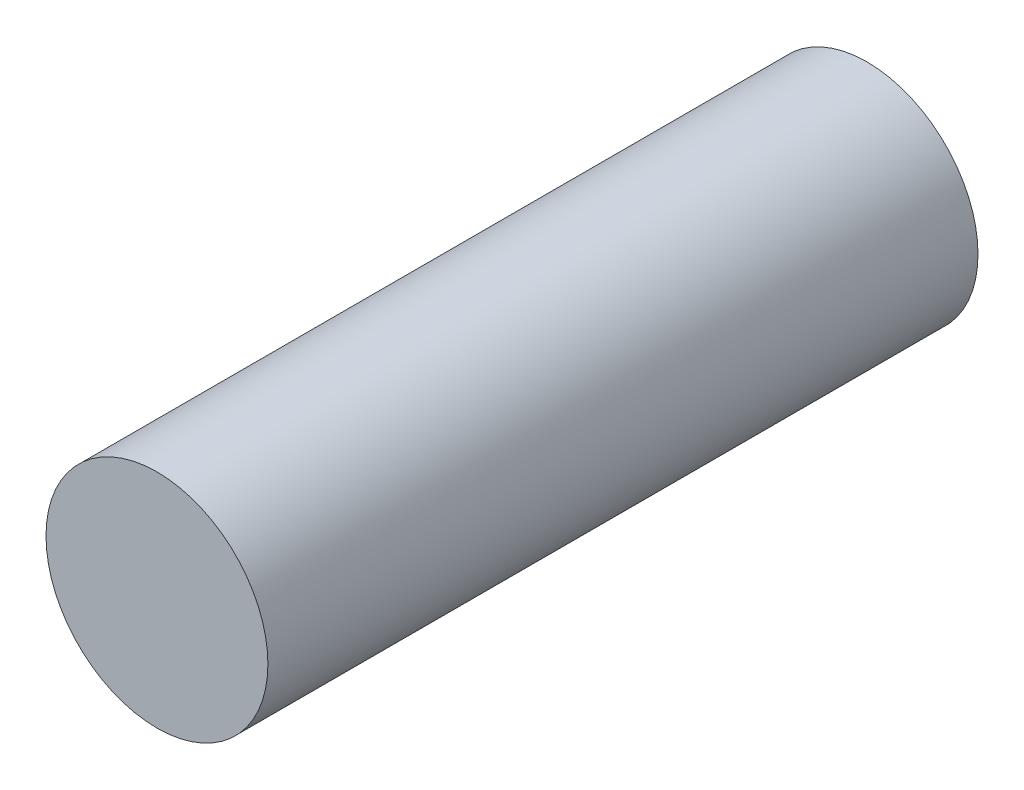
SolidWorks part; units mm, degrees
ref_plane "Plan de face" through (0, 0, 0) normal (0, 0, 1) x (1, 0, 0)
ref_plane "Plan de dessus" through (0, 0, 0) normal (0, 1, 0) x (1, 0, 0)
ref_plane "Plan de droite" through (0, 0, 0) normal (1, 0, 0) x (0, 0, -1)
sketch "Esquisse1" plane through (0, 0, 0) normal (0, 0, 1) x (1, 0, 0)
  circle A0 centre (0, 0) radius 12.5
extrude "Boss.-Extru.1" add sketch "Esquisse1" along normal blind 80 contours A0
